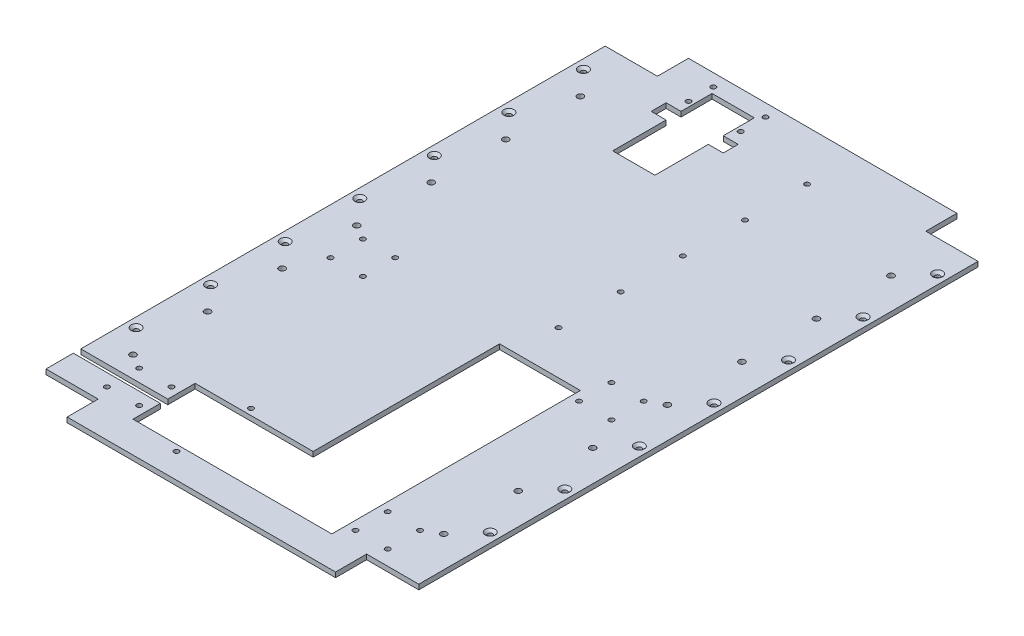
SolidWorks part; units mm, degrees
material "A-玻璃纤维"
ref_plane "前视基准面" through (0, 0, 0) normal (0, 0, 1) x (1, 0, 0)
ref_plane "上视基准面" through (0, 0, 0) normal (0, 1, 0) x (1, 0, 0)
ref_plane "右视基准面" through (0, 0, 0) normal (1, 0, 0) x (0, 0, -1)
sketch "草图1" plane through (0, 0, 0) normal (0, 1, 0) x (1, 0, 0)
  line L1 (-150, 250) -> (150, 250)
  line L2 (-150, 250) -> (-150, -250)
  line L3 (-150, -250) -> (150, -250)
  line L4 (150, 250) -> (150, -250)
  point P4 (150, 0)
  point P6 (0, 250)
  dimension "D1" = 500
  dimension "D2" = 300
extrude "凸台-拉伸1" add sketch "草图1" along normal blind 4
sketch "草图2" plane through (0, 0, 0) normal (0, 1, 0) x (1, 0, 0)
  line L0 (125, 180) -> (125, -180) construction
  line L1 (0, 0) -> (0, 129.5204) construction
  line L2 (-125, 180) -> (-125, -180) construction
  circle A0 centre (125, -180) radius 2.5
  circle A1 centre (125, -120) radius 2.5
  circle A2 centre (125, -60) radius 2.5
  circle A3 centre (125, 0) radius 2.5
  circle A4 centre (125, 60) radius 2.5
  circle A5 centre (125, 120) radius 2.5
  circle A6 centre (125, 180) radius 2.5
  circle A7 centre (-125, 180) radius 2.5
  circle A8 centre (-125, 120) radius 2.5
  circle A9 centre (-125, 60) radius 2.5
  circle A10 centre (-125, 0) radius 2.5
  circle A11 centre (-125, -60) radius 2.5
  circle A12 centre (-125, -120) radius 2.5
  circle A13 centre (-125, -180) radius 2.5
  point P2 (125, 0)
  dimension "D3" = 5
  dimension "D1" = 125
  dimension "D2" = 60
  dimension "D4" = 7
extrude "切除-拉伸5" cut sketch "草图2" along normal through all
sketch "草图4" plane through (0, 0, 0) normal (0, 1, 0) x (1, 0, 0)
  line L0 (150, -250) -> (150, 250) construction
  line L1 (-80, -175) -> (15, -175)
  line L2 (-80, -175) -> (-80, -197)
  line L5 (80, -225) -> (-80, -225)
  line L6 (80, -225) -> (80, -25)
  line L7 (80, -25) -> (15, -25)
  line L8 (15, -175) -> (15, -25)
  line L9 (150, 250) -> (-150, 250) construction
  line L10 (-74, 235) -> (-40, 235)
  line L11 (-80, -197) -> (-150, -197)
  line L12 (-150, 250) -> (-150, -250) construction
  line L13 (-150, -197) -> (-150, -203)
  line L14 (-150, -203) -> (-80, -203)
  line L15 (-90, -200) -> (-183.587, -200) construction
  line L16 (-80, -203) -> (-80, -225)
  line L17 (-150, -250) -> (150, -250) construction
  line L18 (-74, 235) -> (-74, 210)
  line L19 (-74, 155) -> (-40, 155)
  line L21 (-57, 143.3751) -> (-57, 258.7729) construction
  line L22 (-74, 198) -> (-74, 155)
  line L23 (-74, 210) -> (-86, 210)
  line L25 (-74, 198) -> (-86, 198)
  line L26 (-86, 210) -> (-86, 198)
  line L31 (0, 0) -> (0, 348.351) construction
  line L32 (-28, 210) -> (-28, 198)
  line L33 (-40, 198) -> (-28, 198)
  line L34 (-40, 210) -> (-28, 210)
  line L35 (-40, 198) -> (-40, 155)
  line L36 (-40, 235) -> (-40, 210)
  line L37 (0, 0) -> (-150, 0) construction
  line L38 (108, 250) -> (108, 225)
  line L39 (-150, 250) -> (-108, 250)
  line L40 (-150, 250) -> (-150, 225)
  line L41 (-150, 225) -> (-108, 225)
  line L42 (-108, 250) -> (-108, 225)
  line L43 (150, 225) -> (108, 225)
  line L44 (150, 250) -> (150, 225)
  line L45 (150, 250) -> (108, 250)
  line L46 (150, -250) -> (108, -250)
  line L47 (150, -250) -> (150, -225)
  line L48 (150, -225) -> (108, -225)
  line L49 (108, -250) -> (108, -225)
  line L50 (-108, -250) -> (-108, -225)
  line L51 (-150, -225) -> (-108, -225)
  line L52 (-150, -250) -> (-150, -225)
  line L53 (-150, -250) -> (-108, -250)
  circle A0 centre (-78, 240) radius 2
  circle A1 centre (-78, 220) radius 2
  circle A2 centre (-36, 220) radius 2
  circle A3 centre (-36, 240) radius 2
  point P57 (-57, 155)
  point P58 (-57, 235)
  dimension "D11" = 4
  dimension "D1" = 200
  dimension "D2" = 65
  dimension "D3" = 50
  dimension "D4" = 160
  dimension "D5" = 70
  dimension "D6" = 50
  dimension "D7" = 6
  dimension "D8" = 17
  dimension "D9" = 12
  dimension "D10" = 15
  dimension "D12" = 4
  dimension "D13" = 20
  dimension "D14" = 5
  dimension "D15" = 80
  dimension "D16" = 12
  dimension "D17" = 25
  dimension "D18" = 74
  dimension "D19" = 25
  dimension "D20" = 42
extrude "切除-拉伸4" cut sketch "草图4" along normal through all
sketch "草图5" plane through (0, 0, 0) normal (0, 1, 0) x (1, 0, 0)
  line L0 (-80, -175) -> (-80, -197) construction
  line L1 (15, -175) -> (-80, -175) construction
  line L2 (-80, -225) -> (80, -225) construction
  circle A0 centre (-40, -170) radius 2
  circle A1 centre (-40, -230) radius 2
  dimension "D1" = 4
  dimension "D2" = 40
  dimension "D3" = 5
  dimension "D4" = 5
extrude "切除-拉伸6" cut sketch "草图5" along normal blind 10
sketch "草图3" plane through (0, 0, 0) normal (0, 1, 0) x (1, 0, 0)
  line L0 (0, 0) -> (0, -178.6504) construction
  line L1 (-113, -187) -> (-87, -213) construction
  line L2 (-108, -250) -> (108, -250) construction
  line L3 (-113, -33) -> (-87, -7) construction
  line L4 (113, -33) -> (87, -7) construction
  line L5 (113, -187) -> (87, -213) construction
  line L6 (-150, 225) -> (-150, -197) construction
  line L7 (-108, -250) -> (108, -250) construction
  line L8 (-142.5, -160) -> (-142.5, -100) construction
  line L9 (150, -225) -> (150, 225) construction
  circle A0 centre (-113, -187) radius 2
  circle A1 centre (-87, -187) radius 2
  circle A2 centre (-113, -213) radius 2
  circle A3 centre (-87, -213) radius 2
  circle A4 centre (-113, -7) radius 2
  circle A5 centre (-113, -33) radius 2
  circle A6 centre (-87, -7) radius 2
  circle A7 centre (-87, -33) radius 2
  circle A8 centre (87, -33) radius 2
  circle A9 centre (87, -7) radius 2
  circle A10 centre (113, -33) radius 2
  circle A11 centre (113, -7) radius 2
  circle A12 centre (87, -213) radius 2
  circle A13 centre (113, -213) radius 2
  circle A14 centre (87, -187) radius 2
  circle A15 centre (113, -187) radius 2
  circle A16 centre (-142.5, -160) radius 2
  circle A17 centre (-142.5, -100) radius 2
  circle A18 centre (-142.5, -40) radius 2
  circle A19 centre (-142.5, 20) radius 2
  circle A20 centre (-142.5, 80) radius 2
  circle A21 centre (-142.5, 140) radius 2
  circle A22 centre (-142.5, 200) radius 2
  circle A23 centre (142.5, 200) radius 2
  circle A24 centre (142.5, 140) radius 2
  circle A25 centre (142.5, 80) radius 2
  circle A26 centre (142.5, 20) radius 2
  circle A27 centre (142.5, -40) radius 2
  circle A28 centre (142.5, -100) radius 2
  circle A29 centre (142.5, -160) radius 2
  circle A30 centre (27.5, -40) radius 2
  circle A31 centre (27.5, 10) radius 2
  circle A32 centre (27.5, 60) radius 2
  circle A33 centre (27.5, 110) radius 2
  circle A34 centre (27.5, 160) radius 2
  circle A35 centre (27.5, 210) radius 2
  point P8 (-100, -200)
  point P24 (-100, -20)
  dimension "D1" = 4
  dimension "D9" = 4
  dimension "D12" = 4
  dimension "D15" = 4
  dimension "D2" = 26
  dimension "D3" = 26
  dimension "D4" = 100
  dimension "D5" = 50
  dimension "D6" = 180
  dimension "D7" = 26
  dimension "D8" = 26
  dimension "D10" = 7.5
  dimension "D11" = 90
  dimension "D13" = 7
  dimension "D14" = 60
  dimension "D16" = 122.5
  dimension "D17" = 210
  dimension "D19" = 50
  dimension "D18" = 6
extrude "切除-拉伸2" cut sketch "草图3" along normal through all
chamfer "倒角1" distance 2 angle 45 14 edges at (142.5, 4, 158) (142.5, 4, 98) (142.5, 4, 38) (142.5, 4, -22) (142.5, 4, -82) (142.5, 4, -142) (142.5, 4, -202) (-142.5, 4, -198) (-142.5, 4, -138) (-142.5, 4, -78) (-142.5, 4, -18) (-142.5, 4, 42) (-142.5, 4, 102) (-142.5, 4, 162)
